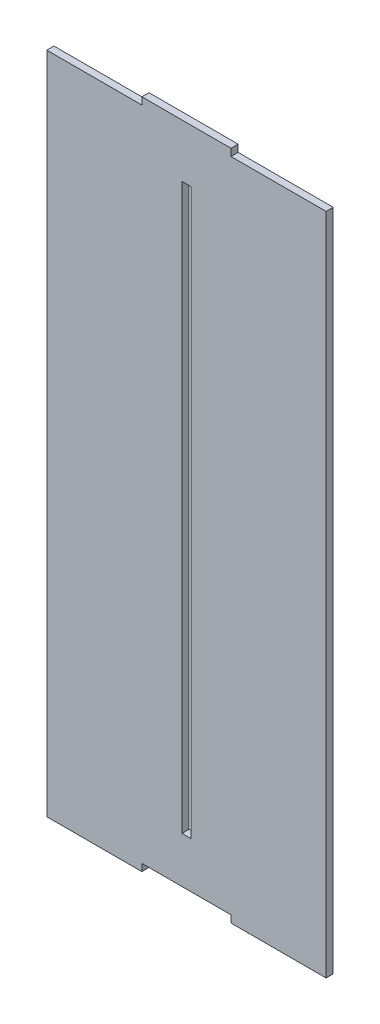
SolidWorks part; units mm, degrees
material "Carvalho"
ref_plane "Plano frontal" through (0, 0, 0) normal (0, 0, 1) x (1, 0, 0)
ref_plane "Plano superior" through (0, 0, 0) normal (0, 1, 0) x (1, 0, 0)
ref_plane "Plano direito" through (0, 0, 0) normal (1, 0, 0) x (0, 0, -1)
sketch "Esboço1" plane through (0, 0, 0) normal (0, 0, 1) x (1, 0, 0)
  line L0 (155, 0) -> (235, 0)
  line L1 (0, 0) -> (80, 0)
  line L2 (0, 0) -> (0, 558.5)
  line L3 (0, 558.5) -> (80, 558.5)
  line L4 (235, 0) -> (235, 558.5)
  line L6 (80, 0) -> (80, 6)
  line L7 (80, 6) -> (155, 6)
  line L8 (155, 0) -> (155, 6)
  line L10 (80, 558.5) -> (80, 564.5)
  line L11 (80, 564.5) -> (155, 564.5)
  line L12 (155, 558.5) -> (155, 564.5)
  line L13 (155, 558.5) -> (235, 558.5)
  line L14 (0, 282.25) -> (235, 282.25) construction
  line L16 (121.25, 44.75) -> (113.75, 44.75)
  line L17 (121.25, 44.75) -> (121.25, 519.75)
  line L18 (121.25, 519.75) -> (113.75, 519.75)
  line L19 (113.75, 44.75) -> (113.75, 519.75)
  line L20 (121.25, 44.75) -> (113.75, 519.75) construction
  line L21 (121.25, 519.75) -> (113.75, 44.75) construction
  point P15 (117.5, 282.25)
  point P20 (0, 0)
  dimension "D1" = 80
  dimension "D2" = 235
  dimension "D3" = 75
  dimension "D4" = 6
  dimension "D5" = 6
  dimension "D6" = 75
  dimension "D7" = 80
  dimension "D8" = 558.5
  dimension "D9" = 475
  dimension "D10" = 7.5
  dimension "D11" = 276.25
extrude "Ressalto-extrusão1" add sketch "Esboço1" along normal blind 6
